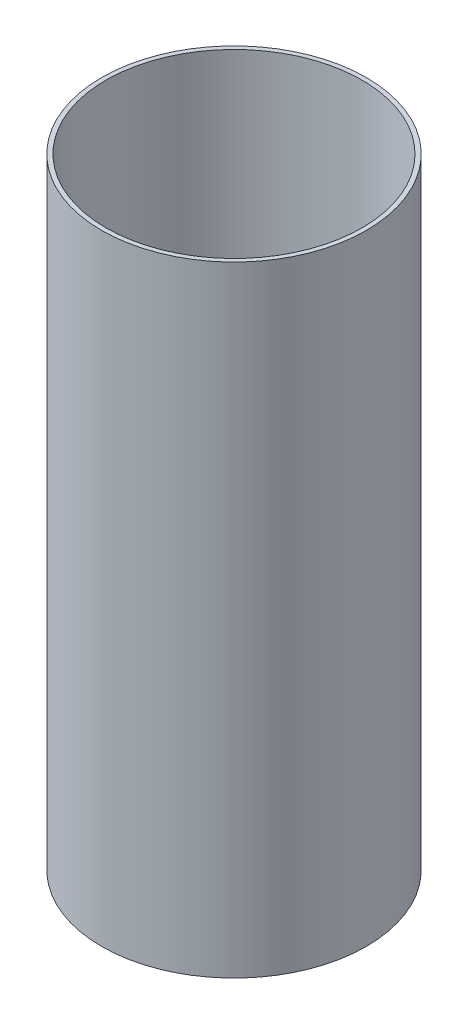
SolidWorks part; units mm, degrees
ref_plane "Front Plane" through (0, 0, 0) normal (0, 0, 1) x (1, 0, 0)
ref_plane "Top Plane" through (0, 0, 0) normal (0, 1, 0) x (1, 0, 0)
ref_plane "Right Plane" through (0, 0, 0) normal (1, 0, 0) x (0, 0, -1)
sketch "Sketch1" plane through (0, 0, 0) normal (0, 1, 0) x (1, 0, 0)
  circle A0 centre (0, 0) radius 76
  circle A1 centre (0, 0) radius 73.5
extrude "Boss-Extrude1" add sketch "Sketch1" along normal blind 356
